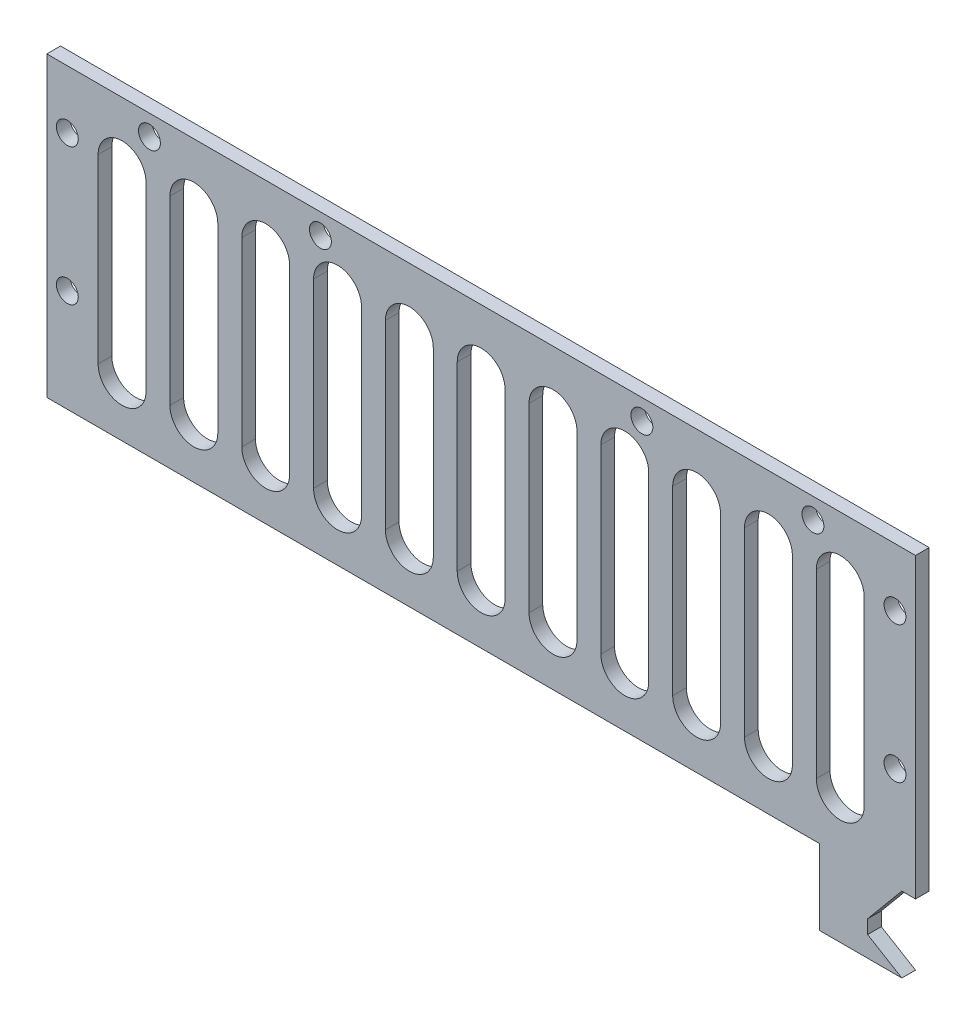
SolidWorks part; units mm, degrees
material "玻纤"
ref_plane "前视基准面" through (0, 0, 0) normal (0, 0, 1) x (1, 0, 0)
ref_plane "上视基准面" through (0, 0, 0) normal (0, 1, 0) x (1, 0, 0)
ref_plane "右视基准面" through (0, 0, 0) normal (1, 0, 0) x (0, 0, -1)
sketch "草图1" plane through (0, 0, 0) normal (0, 0, 1) x (1, 0, 0)
  line L0 (-60.5, 18.25) -> (-60.5, -21.75) construction
  line L1 (-63.5, -21.75) -> (63.5, -21.75)
  line L2 (-63.5, -21.75) -> (-63.5, 21.75)
  line L3 (-63.5, 21.75) -> (63.5, 21.75)
  line L4 (63.5, -21.75) -> (63.5, 21.75)
  line L5 (-63.5, -21.75) -> (63.5, 21.75) construction
  line L6 (-63.5, 21.75) -> (63.5, -21.75) construction
  line L7 (-57.5, 18.25) -> (-63.5, 18.25)
  line L8 (-57.5, 18.25) -> (-57.5, -21.75)
  line L9 (-57.5, -21.75) -> (-63.5, -21.75)
  line L10 (-63.5, 18.25) -> (-63.5, -21.75)
  line L11 (-57.5, 18.25) -> (-63.5, -21.75) construction
  line L12 (-57.5, -21.75) -> (-63.5, 18.25) construction
  line L13 (0, 0) -> (0, -21.75) construction
  line L14 (57.5, -21.75) -> (63.5, 18.25) construction
  line L15 (57.5, 18.25) -> (63.5, -21.75) construction
  line L16 (60.5, 18.25) -> (60.5, -21.75) construction
  line L17 (63.5, 18.25) -> (63.5, -21.75)
  line L18 (57.5, -21.75) -> (63.5, -21.75)
  line L19 (57.5, 18.25) -> (57.5, -21.75)
  line L20 (57.5, 18.25) -> (63.5, 18.25)
  line L21 (-63.5, 18.75) -> (63.5, 18.75) construction
  circle A0 centre (-60.5, 13.25) radius 1.6
  circle A1 centre (-60.5, -6.75) radius 1.6
  circle A2 centre (60.5, -6.75) radius 1.6
  circle A3 centre (60.5, 13.25) radius 1.6
  circle A4 centre (-48.5, 18.75) radius 1.6
  circle A5 centre (-23.5, 18.75) radius 1.6
  circle A6 centre (23.5, 18.75) radius 1.6
  circle A7 centre (48.5, 18.75) radius 1.6
  point P0 (0, 0)
  point P5 (-60.5, -1.75)
  point P27 (60.5, -1.75)
  dimension "D3" = 15
  dimension "D4" = 20
  dimension "D5" = 5
  dimension "D7" = 3.2
  dimension "D8" = 3.2
  dimension "D10" = 15
  dimension "D12" = 3.2
  dimension "D1" = 6
  dimension "D2" = 127
  dimension "D6" = 8.5
  dimension "D9" = 3
  dimension "D11" = 25
extrude "凸台-拉伸1" add sketch "草图1" along normal blind 2 contours L19 L20 L4 L3 L2 L7 L8 L1 | L20 L19 L1 L4 A2 A3 | L8 L7 L2 L1 A1 A0
sketch "草图2" plane through (0, 0, 2) normal (0, 0, 1) x (1, 0, 0)
  line L0 (0, 12.75) -> (0, -13.75) construction
  line L1 (3.5, 12.75) -> (3.5, -13.75)
  line L2 (-3.5, 12.75) -> (-3.5, -13.75)
  line L3 (-63.5, -21.75) -> (63.5, -21.75) construction
  line L4 (-63.5, 21.75) -> (63.5, 21.75) construction
  line L5 (0, -0.5) -> (-25.8037, -0.5) construction
  line L6 (10.5, 12.75) -> (10.5, -13.75) construction
  line L7 (14, 12.75) -> (14, -13.75)
  line L8 (7, 12.75) -> (7, -13.75)
  line L9 (21, 12.75) -> (21, -13.75) construction
  line L10 (24.5, 12.75) -> (24.5, -13.75)
  line L11 (17.5, 12.75) -> (17.5, -13.75)
  line L12 (31.5, 12.75) -> (31.5, -13.75) construction
  line L13 (35, 12.75) -> (35, -13.75)
  line L14 (28, 12.75) -> (28, -13.75)
  line L15 (42, 12.75) -> (42, -13.75) construction
  line L16 (45.5, 12.75) -> (45.5, -13.75)
  line L17 (38.5, 12.75) -> (38.5, -13.75)
  line L18 (-10.5, 12.75) -> (-10.5, -13.75) construction
  line L19 (-7, 12.75) -> (-7, -13.75)
  line L20 (-14, 12.75) -> (-14, -13.75)
  line L21 (-21, 12.75) -> (-21, -13.75) construction
  line L22 (-17.5, 12.75) -> (-17.5, -13.75)
  line L23 (-24.5, 12.75) -> (-24.5, -13.75)
  line L24 (-31.5, 12.75) -> (-31.5, -13.75) construction
  line L25 (-28, 12.75) -> (-28, -13.75)
  line L26 (-35, 12.75) -> (-35, -13.75)
  line L27 (-42, 12.75) -> (-42, -13.75) construction
  line L28 (-38.5, 12.75) -> (-38.5, -13.75)
  line L29 (-45.5, 12.75) -> (-45.5, -13.75)
  line L30 (-52.5, 12.75) -> (-52.5, -13.75) construction
  line L31 (-49, 12.75) -> (-49, -13.75)
  line L32 (-56, 12.75) -> (-56, -13.75)
  line L33 (52.5, 12.75) -> (52.5, -13.75) construction
  line L34 (56, 12.75) -> (56, -13.75)
  line L35 (49, 12.75) -> (49, -13.75)
  arc A0 (3.5, 12.75) -> (-3.5, 12.75) centre (0, 12.75) ccw
  arc A1 (-3.5, -13.75) -> (3.5, -13.75) centre (0, -13.75) ccw
  arc A2 (14, 12.75) -> (7, 12.75) centre (10.5, 12.75) ccw
  arc A3 (7, -13.75) -> (14, -13.75) centre (10.5, -13.75) ccw
  arc A4 (24.5, 12.75) -> (17.5, 12.75) centre (21, 12.75) ccw
  arc A5 (17.5, -13.75) -> (24.5, -13.75) centre (21, -13.75) ccw
  arc A6 (35, 12.75) -> (28, 12.75) centre (31.5, 12.75) ccw
  arc A7 (28, -13.75) -> (35, -13.75) centre (31.5, -13.75) ccw
  arc A8 (45.5, 12.75) -> (38.5, 12.75) centre (42, 12.75) ccw
  arc A9 (38.5, -13.75) -> (45.5, -13.75) centre (42, -13.75) ccw
  arc A10 (-7, 12.75) -> (-14, 12.75) centre (-10.5, 12.75) ccw
  arc A11 (-14, -13.75) -> (-7, -13.75) centre (-10.5, -13.75) ccw
  arc A12 (-17.5, 12.75) -> (-24.5, 12.75) centre (-21, 12.75) ccw
  arc A13 (-24.5, -13.75) -> (-17.5, -13.75) centre (-21, -13.75) ccw
  arc A14 (-28, 12.75) -> (-35, 12.75) centre (-31.5, 12.75) ccw
  arc A15 (-35, -13.75) -> (-28, -13.75) centre (-31.5, -13.75) ccw
  arc A16 (-38.5, 12.75) -> (-45.5, 12.75) centre (-42, 12.75) ccw
  arc A17 (-45.5, -13.75) -> (-38.5, -13.75) centre (-42, -13.75) ccw
  arc A18 (-49, 12.75) -> (-56, 12.75) centre (-52.5, 12.75) ccw
  arc A19 (-56, -13.75) -> (-49, -13.75) centre (-52.5, -13.75) ccw
  arc A20 (56, 12.75) -> (49, 12.75) centre (52.5, 12.75) ccw
  arc A21 (49, -13.75) -> (56, -13.75) centre (52.5, -13.75) ccw
  point P3 (0, -0.5)
  point P17 (10.5, -0.5)
  point P24 (21, -0.5)
  point P31 (31.5, -0.5)
  point P38 (42, -0.5)
  point P45 (-10.5, -0.5)
  point P52 (-21, -0.5)
  point P59 (-31.5, -0.5)
  point P66 (-42, -0.5)
  point P72 (-52.5, -0.5)
  point P79 (52.5, -0.5)
  dimension "D1" = 3.5
  dimension "D2" = 8
  dimension "D3" = 9
  dimension "D4" = 6
  dimension "D6" = 10.5
  dimension "D7" = 10.5
  dimension "D5" = 6
extrude "切除-拉伸1" cut sketch "草图2" against normal blind 2
sketch "草图3" plane through (0, 0, 2) normal (0, 0, 1) x (1, 0, 0)
  line L0 (49.5, -21.75) -> (49.5, -32.75)
  line L1 (49.5, -32.75) -> (61.5, -32.75)
  line L2 (61.5, -32.75) -> (56.5, -29.75)
  line L4 (-63.5, -21.75) -> (63.5, -21.75) construction
  line L5 (61.5, -21.75) -> (49.5, -21.75)
  line L6 (56.5, -29.75) -> (56.5, -27.75)
  line L7 (56.5, -27.75) -> (61.5, -21.75)
  line L8 (63.5, -21.75) -> (63.5, 21.75) construction
  dimension "D1" = 11
  dimension "D2" = 12
  dimension "D3" = 5
  dimension "D4" = 2
  dimension "D5" = 2
  dimension "D6" = 3
extrude "凸台-拉伸2" add sketch "草图3" against normal up to surface (2 mm away) up to face at (10.5, -0.5, 0)
